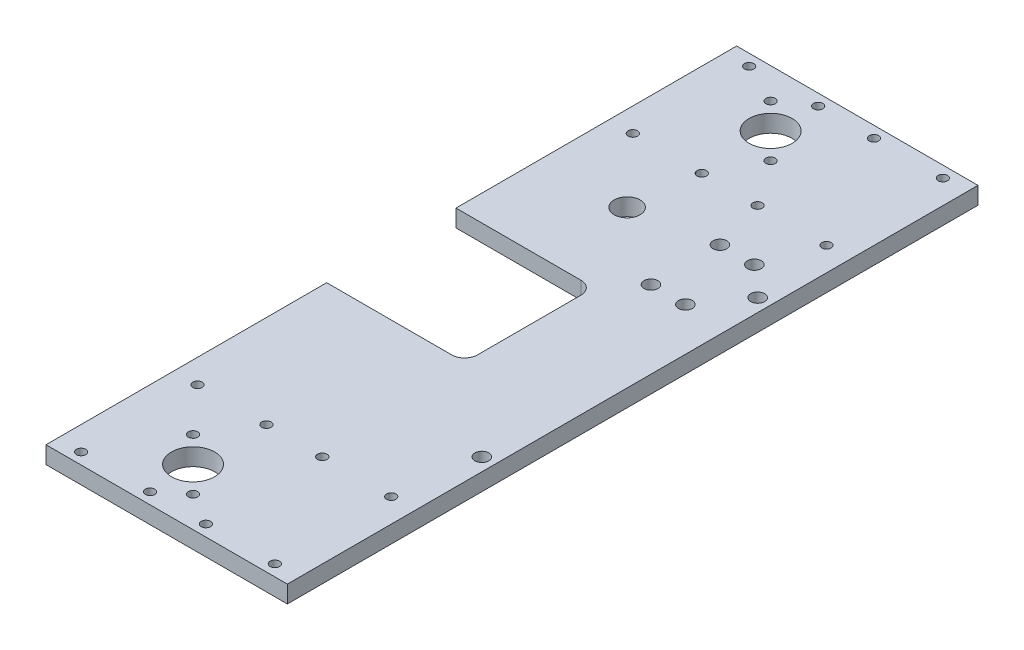
SolidWorks part; units mm, degrees
ref_plane "Front Plane" through (0, 0, 0) normal (0, 0, 1) x (1, 0, 0)
ref_plane "Top Plane" through (0, 0, 0) normal (0, 1, 0) x (1, 0, 0)
ref_plane "Right Plane" through (0, 0, 0) normal (1, 0, 0) x (0, 0, -1)
sketch "Sketch1" plane through (0, 0, 0) normal (0, 1, 0) x (1, 0, 0)
  line L0 (-22.1867, -110.036) -> (-22.1867, -213.414)
  line L1 (-22.1867, 40.967) -> (66.7133, 40.967)
  line L2 (-22.1867, 40.967) -> (-22.1867, -62.411)
  line L3 (-22.1867, -213.414) -> (66.7133, -213.414)
  line L4 (66.7133, 40.967) -> (66.7133, -213.414)
  line L5 (-22.1867, -62.411) -> (23.8508, -62.411)
  line L7 (-22.1867, -110.036) -> (23.8508, -110.036)
  line L8 (28.6133, -67.1735) -> (28.6133, -105.2735)
  arc A0 (23.8508, -110.036) -> (28.6133, -105.2735) centre (23.8508, -105.2735) ccw
  arc A1 (23.8508, -62.411) -> (28.6133, -67.1735) centre (23.8508, -67.1735) cw
  circle A2 centre (9.1061, -30.661) radius 4.7625
  circle A3 centre (11.1508, 20.139) radius 7.9375
  circle A4 centre (11.1508, -192.586) radius 7.9375
  point P12 (28.6133, -62.411)
  dimension "D6" = 4.7625
  dimension "D8" = 19.5072
  dimension "D9" = 9.525
  dimension "D10" = 15.875
  dimension "D11" = 17.4625
  dimension "D12" = 50.8
  dimension "D13" = 15.875
  dimension "D14" = 17.4625
  dimension "D15" = 82.55
  dimension "D1" = 88.9
  dimension "D2" = 254.381
  dimension "D3" = 103.378
  dimension "D4" = 151.003
  dimension "D5" = 50.8
  dimension "D7" = 31.75
extrude "Boss-Extrude1" add sketch "Sketch1" along normal blind 6.35
hole_wizard "#8-32 Tapped Hole1" positions "Sketch3" profile "Sketch2" tap size "#8-32" standard "ANSI Inch" end condition through all
sketch "Sketch3" plane through (0, 6.35, 0) normal (0, 1, 0) x (1, 0, 0)
  line L0 (-0.711, -161.5393) -> (-0.711, -223.9632) construction
  line L3 (-49.1532, -187.8235) -> (82.4408, -187.8235) construction
  line L6 (-22.1867, -110.036) -> (-22.1867, -213.414) construction
  line L7 (-22.1867, -213.414) -> (66.7133, -213.414) construction
  line L8 (22.2633, -213.414) -> (22.2633, -127.2607) construction
  line L11 (66.7133, -86.2235) -> (-81.0194, -86.2235) construction
  line L12 (66.7133, -213.414) -> (66.7133, 40.967) construction
  point P0 (-13.411, -166.3922)
  point P34 (11.989, -166.3922)
  point P35 (11.989, -209.2547)
  point P36 (-13.411, -209.2547)
  point P37 (57.9376, -209.2547)
  point P38 (32.5376, -209.2547)
  point P39 (32.5376, -166.3922)
  point P40 (57.9376, -166.3922)
  point P52 (32.5376, -6.0547)
  point P53 (57.9376, -6.0547)
  point P54 (57.9376, 36.8078)
  point P55 (32.5376, 36.8078)
  point P56 (-13.411, 36.8078)
  point P57 (11.989, 36.8078)
  point P58 (11.989, -6.0547)
  point P59 (-13.411, -6.0547)
  dimension "D1" = 25.4
  dimension "D2" = 42.8625
  dimension "D3" = 21.4757
  dimension "D4" = 25.5905
sketch "Sketch2" plane through (-13.411, 6.35, 166.3922) normal (1, 0, 0) x (0, 0, 1)
  line L0 (0, 0) -> (0, 6.35)
  line L1 (0, 6.35) -> (1.7272, 6.35)
  line L2 (1.7272, 6.35) -> (1.7272, 0)
  line L5 (1.7272, 0) -> (0, 0)
  line L11 (0, -6.35) -> (0, 107.95) construction
  dimension "Thru Tap Drill Dia." = 3.4544
  dimension "Thru Tap Drill Depth" = 6.35
cosmetic thread "Hole Thread1" parameters "D2"=4.1656
cosmetic thread "Hole Thread2" parameters "D2"=4.1656
cosmetic thread "Hole Thread3" parameters "D2"=4.1656
cosmetic thread "Hole Thread4" parameters "D2"=4.1656
cosmetic thread "Hole Thread5" parameters "D2"=4.1656
cosmetic thread "Hole Thread6" parameters "D2"=4.1656
cosmetic thread "Hole Thread7" parameters "D2"=4.1656
cosmetic thread "Hole Thread8" parameters "D2"=4.1656
cosmetic thread "Hole Thread9" parameters "D2"=4.1656
cosmetic thread "Hole Thread10" parameters "D2"=4.1656
cosmetic thread "Hole Thread11" parameters "D2"=4.1656
cosmetic thread "Hole Thread12" parameters "D2"=4.1656
cosmetic thread "Hole Thread13" parameters "D2"=4.1656
cosmetic thread "Hole Thread14" parameters "D2"=4.1656
cosmetic thread "Hole Thread15" parameters "D2"=4.1656
cosmetic thread "Hole Thread17" parameters "D2"=4.1656
hole_wizard "#10 Clearance Hole1" positions "Sketch6" profile "Sketch4" hole size "#10" standard "ANSI Inch" end condition through all
sketch "Sketch6" plane through (0, 6.35, 0) normal (0, 1, 0) x (1, 0, 0)
  line L1 (28.6133, -67.1735) -> (28.6133, -105.2735) construction
  line L3 (28.6133, -86.2235) -> (84.9185, -86.2235) construction
  line L6 (66.7133, -213.414) -> (66.7133, 40.967) construction
  line L7 (44.4883, -15.0817) -> (44.4883, -59.8259) construction
  line L10 (-12.48, -38.2175) -> (39.5419, -38.2175) construction
  line L13 (66.7133, 40.967) -> (-22.1867, 40.967) construction
  point P0 (61.9508, -137.0235)
  point P2 (38.1383, -25.5175)
  point P22 (61.9508, -35.4235)
  point P36 (50.8383, -25.5175)
  point P37 (50.8383, -50.9175)
  point P38 (38.1383, -50.9175)
  dimension "D1" = 101.6
  dimension "D2" = 4.7625
  dimension "D3" = 79.1845
  dimension "D4" = 15.875
  dimension "D5" = 12.7
  dimension "D6" = 25.4
sketch "Sketch4" plane through (61.9508, 6.35, 137.0235) normal (1, 0, 0) x (0, 0, 1)
  line L0 (0, 0) -> (0, 6.35)
  line L1 (0, 6.35) -> (2.5527, 6.35)
  line L2 (2.5527, 6.35) -> (2.5527, 0)
  line L5 (2.5527, 0) -> (0, 0)
  line L11 (0, -6.35) -> (0, 107.95) construction
  dimension "Thru Hole Dia." = 5.1054
  dimension "Thru Hole Depth" = 6.35
hole_wizard "#8-32 Tapped Hole2" positions "Sketch8" profile "Sketch7" tap size "#8-32" standard "ANSI Inch" end condition through all
sketch "Sketch8" plane through (0, 6.35, 0) normal (0, 1, 0) x (1, 0, 0)
  circle A0 centre (11.1508, 20.139) radius 7.9375 construction
  circle A1 centre (11.1508, -192.586) radius 7.9375 construction
  point P0 (1.6258, 29.664)
  point P2 (20.6758, 10.614)
  point P7 (1.6258, -183.061)
  point P9 (20.6758, -202.111)
  dimension "D7" = 9.525
  dimension "D1" = 9.525
  dimension "D2" = 9.525
  dimension "D3" = 9.525
  dimension "D4" = 9.525
  dimension "D5" = 9.525
  dimension "D6" = 9.525
  dimension "D8" = 9.525
sketch "Sketch7" plane through (1.6258, 6.35, -29.664) normal (1, 0, 0) x (0, 0, 1)
  line L0 (0, 0) -> (0, 6.35)
  line L1 (0, 6.35) -> (1.7272, 6.35)
  line L2 (1.7272, 6.35) -> (1.7272, 0)
  line L5 (1.7272, 0) -> (0, 0)
  line L11 (0, -6.35) -> (0, 107.95) construction
  dimension "Thread Major Dia." = 3.4544
  dimension "Thru Tap Drill Depth" = 6.35
